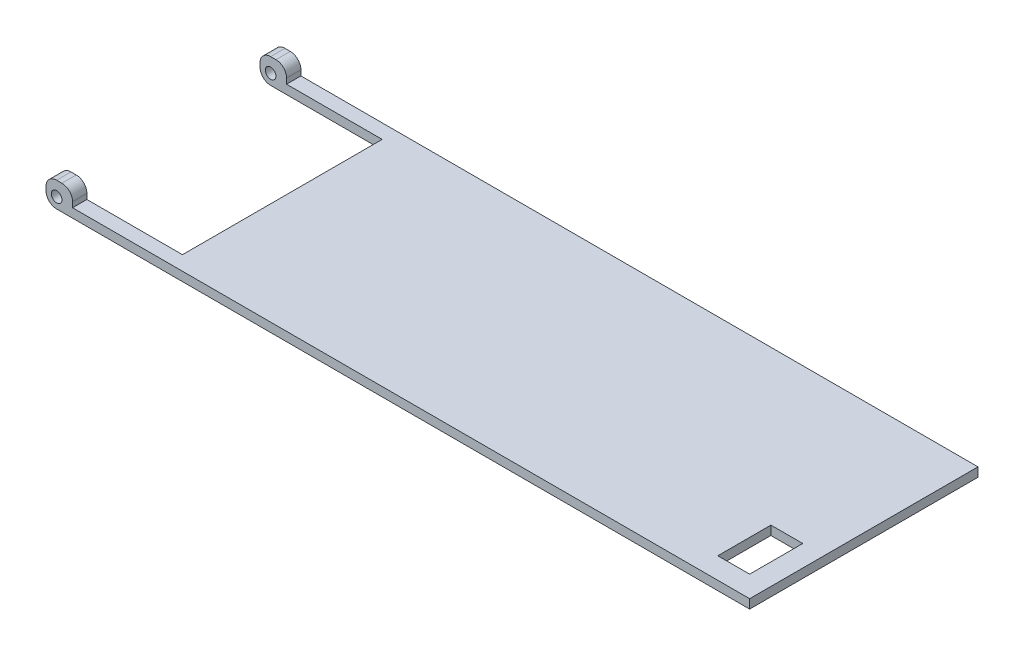
SolidWorks part; units mm, degrees
ref_plane "Front Plane" through (0, 0, 0) normal (0, 0, 1) x (1, 0, 0)
ref_plane "Top Plane" through (0, 0, 0) normal (0, 1, 0) x (1, 0, 0)
ref_plane "Right Plane" through (0, 0, 0) normal (1, 0, 0) x (0, 0, -1)
sketch "Sketch1" plane through (0, 0, 0) normal (0, 1, 0) x (1, 0, 0)
  line L1 (-66.25, -21.5) -> (66.25, -21.5)
  line L2 (-66.25, -21.5) -> (-66.25, 21.5)
  line L3 (-66.25, 21.5) -> (66.25, 21.5)
  line L4 (66.25, -21.5) -> (66.25, 21.5)
  line L5 (-66.25, -21.5) -> (66.25, 21.5) construction
  line L6 (-66.25, 21.5) -> (66.25, -21.5) construction
  point P0 (0, 0)
  dimension "D1" = 132.5
  dimension "D2" = 43
extrude "Boss-Extrude1" add sketch "Sketch1" along normal blind 1.7
sketch "Sketch2" plane through (0, 1.7, 0) normal (0, 1, 0) x (1, 0, 0)
  line L0 (-66.25, 21.5) -> (-66.25, -21.5) construction
  line L1 (-66.25, -18.8) -> (-43.25, -18.8)
  line L2 (-66.25, -18.8) -> (-66.25, 18.8)
  line L3 (-66.25, 18.8) -> (-43.25, 18.8)
  line L4 (-43.25, -18.8) -> (-43.25, 18.8)
  line L5 (-66.25, -21.5) -> (66.25, -21.5) construction
  line L6 (66.25, 21.5) -> (-66.25, 21.5) construction
  dimension "D1" = 2.7
  dimension "D2" = 2.7
  dimension "D3" = 23
extrude "Cut-Extrude1" cut sketch "Sketch2" against normal up to vertex (1.7 mm away)
sketch "Sketch4" plane through (0, 1.7, 0) normal (0, 1, 0) x (1, 0, 0)
  line L0 (-66.25, -21.5) -> (66.25, -21.5) construction
  line L1 (-66.25, -18.8) -> (-61.25, -18.8)
  line L2 (-66.25, -18.8) -> (-66.25, -21.5)
  line L3 (-66.25, -21.5) -> (-61.25, -21.5)
  line L4 (-61.25, -18.8) -> (-61.25, -21.5)
  dimension "D1" = 5
extrude "Boss-Extrude2" add sketch "Sketch4" along normal blind 3
sketch "Sketch5" plane through (0, 0, 21.5) normal (0, 0, 1) x (1, 0, 0)
  line L0 (-66.25, 0) -> (66.25, 0) construction
  line L1 (-66.25, 4.7) -> (-66.25, 0) construction
  circle A0 centre (-64.25, 2) radius 1
  dimension "D3" = 2
  dimension "D1" = 2
  dimension "D2" = 2
extrude "Cut-Extrude2" cut sketch "Sketch5" against normal up to vertex (2.7 mm away) contours A0
fillet "Fillet1" radius 2 3 edges at (-66.25, 0, 20.15) (-66.25, 4.7, 20.15) (-61.25, 4.7, 20.15)
ref_plane "Plane1" through (0, 0, 0) normal (0, 0, 1) x (1, 0, 0)
mirror "Mirror2" about plane through (0, 0, 0) normal (0, 0, 1) of "Boss-Extrude2", "Cut-Extrude2", "Fillet1"
sketch "Sketch10" plane through (0, 1.7, 0) normal (0, 1, 0) x (1, 0, 0)
  line L0 (66.25, -21.5) -> (66.25, 21.5) construction
  line L1 (56.25, -17.5) -> (62.25, -17.5)
  line L2 (56.25, -17.5) -> (56.25, -7.5)
  line L3 (56.25, -7.5) -> (62.25, -7.5)
  line L4 (62.25, -17.5) -> (62.25, -7.5)
  line L5 (56.25, -17.5) -> (62.25, -7.5) construction
  line L6 (56.25, -7.5) -> (62.25, -17.5) construction
  line L8 (-61.25, -21.5) -> (66.25, -21.5) construction
  point P0 (59.25, -12.5)
  dimension "D1" = 4
  dimension "D2" = 6
  dimension "D3" = 4
  dimension "D4" = 10
extrude "Cut-Extrude3" cut sketch "Sketch10" against normal up to vertex (1.7 mm away) up to point (66.25, 0, -21.5)
